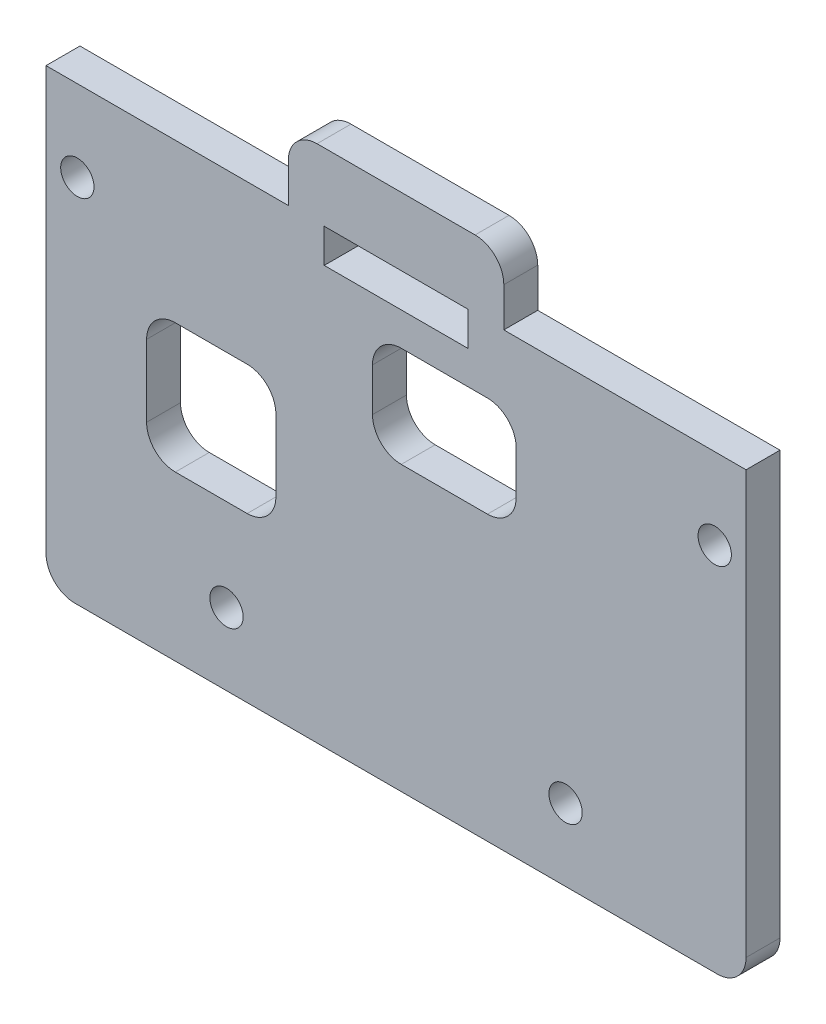
SolidWorks part; units mm, degrees
material "Acrylic (Medium-high impact)"
ref_plane "Front Plane" through (0, 0, 0) normal (0, 0, 1) x (1, 0, 0)
ref_plane "Top Plane" through (0, 0, 0) normal (0, 1, 0) x (1, 0, 0)
ref_plane "Right Plane" through (0, 0, 0) normal (1, 0, 0) x (0, 0, -1)
sketch "Sketch1" plane through (0, 0, 0) normal (0, 0, 1) x (1, 0, 0)
  line L1 (0, 0) -> (61.88, 0)
  line L2 (0, 0) -> (0, 45.878)
  line L3 (0, 45.878) -> (61.88, 45.878)
  line L4 (61.88, 0) -> (61.88, 45.878)
  dimension "D1" = 61.88
  dimension "D2" = 45.878
extrude "Boss-Extrude1" add sketch "Sketch1" along normal blind 3
hole_wizard "#32 (0.116) Diameter Hole1" positions "Sketch5" profile "Sketch2" hole size "#32" standard "ANSI Inch" end condition through all
sketch "Sketch5" plane through (0, 0, 3) normal (0, 0, 1) x (1, 0, 0)
  line L0 (61.88, 45.878) -> (0, 45.878) construction
  line L1 (30.94, 45.878) -> (30.94, 0) construction
  line L2 (0, 0) -> (61.88, 0) construction
  line L3 (0, 45.878) -> (0, 0) construction
  line L4 (61.88, 0) -> (61.88, 45.878) construction
  line L5 (61.88, 45.878) -> (0, 45.878) construction
  point P0 (15.954, 6.374)
  point P2 (45.926, 6.374)
  point P19 (59.11, 32.7152)
  point P21 (2.77, 32.7152)
  dimension "D1" = 39.504
  dimension "D2" = 14.986
  dimension "D3" = 14.986
  dimension "D4" = 2.77
  dimension "D5" = 2.77
  dimension "D6" = 13.1628
  dimension "D7" = 13.1628
sketch "Sketch2" plane through (15.954, 6.374, 3) normal (1, 0, 0) x (0, -1, 0)
  line L0 (0, 0) -> (0, 3)
  line L1 (0, 3) -> (1.4732, 3)
  line L2 (1.4732, 3) -> (1.4732, 0)
  line L5 (1.4732, 0) -> (0, 0)
  line L11 (0, -6.35) -> (0, 107.95) construction
  dimension "Thru Hole Dia." = 2.9464
  dimension "Thru Hole Depth" = 3
fillet "Fillet1" radius 2.54 2 edges at (0, 0, 1.5) (61.88, 0, 1.5)
sketch "Sketch6" plane through (0, 0, 0) normal (0, 0, -1) x (-1, 0, 0)
  line L1 (-37.2928, 39.878) -> (-24.5928, 39.878)
  line L2 (-37.2928, 39.878) -> (-37.2928, 36.878)
  line L3 (-37.2928, 36.878) -> (-24.5928, 36.878)
  line L4 (-24.5928, 39.878) -> (-24.5928, 36.878)
  line L5 (-61.88, 45.878) -> (0, 45.878) construction
  line L9 (0, 45.878) -> (0, 2.54) construction
  dimension "D1" = 12.7
  dimension "D2" = 3
  dimension "D3" = 24.5928
  dimension "D4" = 6
extrude "Cut-Extrude1" cut sketch "Sketch6" against normal blind 3
sketch "Sketch7" plane through (0, 0, 0) normal (0, 0, -1) x (-1, 0, 0)
  line L0 (-61.88, 45.878) -> (0, 45.878) construction
  line L1 (-41.56, 33.94) -> (-28.86, 33.94)
  line L2 (-41.56, 33.94) -> (-41.56, 25.05)
  line L3 (-41.56, 25.05) -> (-28.86, 25.05)
  line L4 (-28.86, 33.94) -> (-28.86, 25.05)
  line L5 (-20.32, 25.908) -> (-8.89, 25.908)
  line L6 (-20.32, 25.908) -> (-20.32, 14.478)
  line L7 (-20.32, 14.478) -> (-8.89, 14.478)
  line L8 (-8.89, 25.908) -> (-8.89, 14.478)
  line L9 (-61.88, 2.54) -> (-61.88, 45.878) construction
  line L10 (0, 45.878) -> (0, 2.54) construction
  point P12 (-30.94, 45.878)
  dimension "D1" = 11.938
  dimension "D2" = 20.828
  dimension "D3" = 20.32
  dimension "D4" = 33.02
  dimension "D5" = 19.97
  dimension "D6" = 31.4
  dimension "D7" = 8.89
  dimension "D8" = 20.32
extrude "Cut-Extrude2" cut sketch "Sketch7" against normal through all
fillet "Fillet2" radius 2.54 8 edges at (20.32, 14.478, 1.5) (8.89, 14.478, 1.5) (8.89, 25.908, 1.5) (20.32, 25.908, 1.5) (41.56, 25.05, 1.5) (28.86, 25.05, 1.5) (28.86, 33.94, 1.5) (41.56, 33.94, 1.5)
sketch "Sketch9" plane through (0, 0, 0) normal (0, 0, -1) x (-1, 0, 0)
  line L0 (-61.88, 45.878) -> (0, 45.878) construction
  line L2 (-61.88, 45.878) -> (-40.4678, 45.878)
  line L4 (-61.88, 45.878) -> (-61.88, 39.878)
  line L5 (-61.88, 39.878) -> (-40.4678, 39.878)
  line L6 (-40.4678, 45.878) -> (-40.4678, 39.878)
  line L7 (-21.4178, 45.878) -> (0, 45.878)
  line L8 (-21.4178, 45.878) -> (-21.4178, 39.878)
  line L9 (-21.4178, 39.878) -> (0, 39.878)
  line L10 (0, 45.878) -> (0, 39.878)
  dimension "D1" = 6
  dimension "D2" = 6
  dimension "D3" = 19.05
  dimension "D4" = 21.4122
extrude "Cut-Extrude3" cut sketch "Sketch9" against normal through all
fillet "Fillet4" radius 2.54 2 edges at (40.4678, 45.878, 1.5) (21.4178, 45.878, 1.5)
